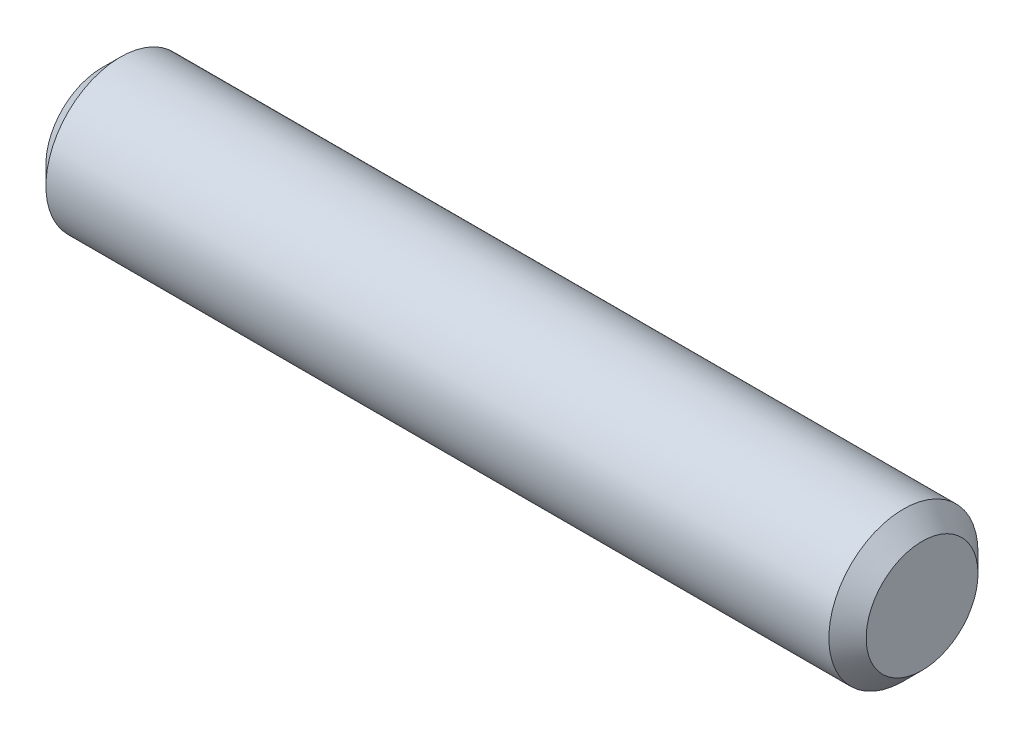
SolidWorks part; units mm, degrees
ref_plane "Front Plane" through (0, 0, 0) normal (0, 0, 1) x (1, 0, 0)
ref_plane "Top Plane" through (0, 0, 0) normal (0, 1, 0) x (1, 0, 0)
ref_plane "Right Plane" through (0, 0, 0) normal (1, 0, 0) x (0, 0, -1)
sketch "Sketch1" plane through (0, 0, 0) normal (1, 0, 0) x (0, 0, -1)
  circle A0 centre (0, 0) radius 2
  dimension "D1" = 4
extrude "Boss-Extrude1" add sketch "Sketch1" along normal mid plane 22
chamfer "Chamfer1" distance 0.5 angle 45 2 edges at (-11, 0, -2) (11, 0, -2)
